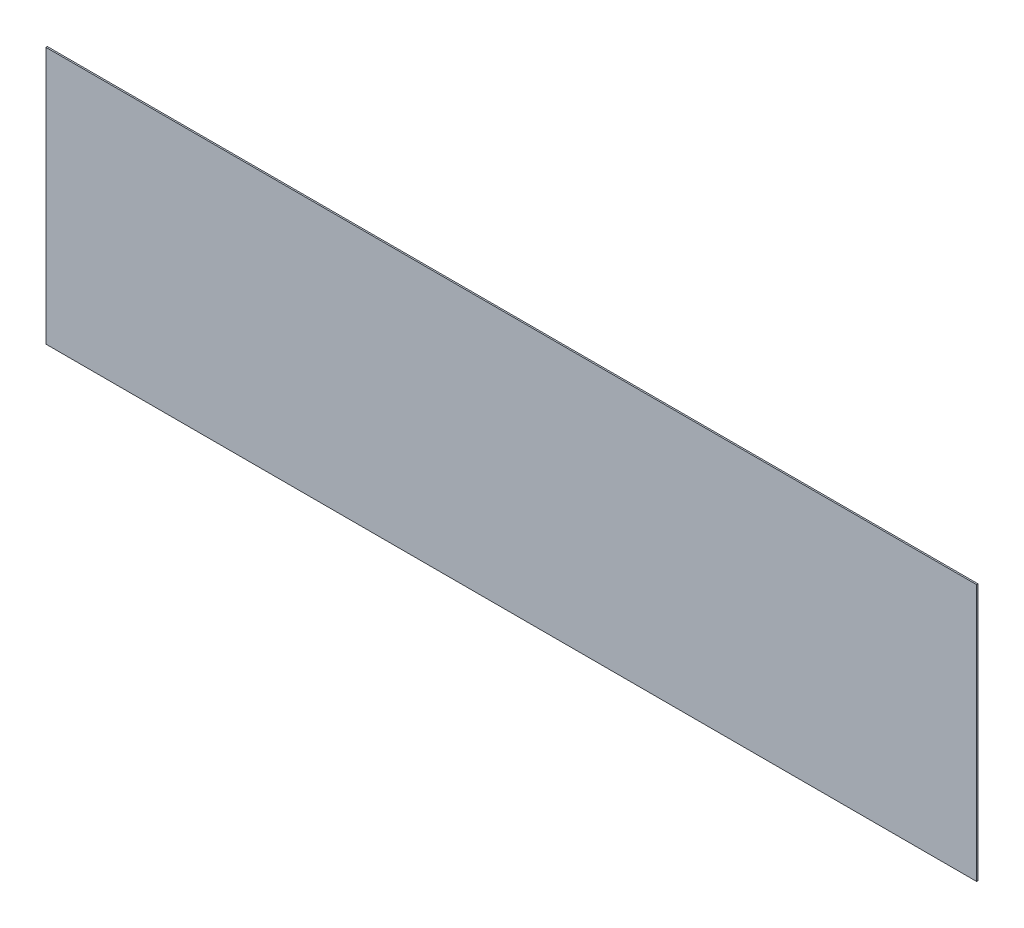
SolidWorks part; units mm, degrees
ref_plane "Front Plane" through (0, 0, 0) normal (0, 0, 1) x (1, 0, 0)
ref_plane "Top Plane" through (0, 0, 0) normal (0, 1, 0) x (1, 0, 0)
ref_plane "Right Plane" through (0, 0, 0) normal (1, 0, 0) x (0, 0, -1)
other "Configuration Table"
sketch "Sketch1" plane through (0, 0, 0) normal (0, 0, 1) x (1, 0, 0)
  line L1 (702, 1469) -> (1350, 1469)
  line L2 (702, 1469) -> (702, 1648)
  line L3 (702, 1648) -> (1350, 1648)
  line L4 (1350, 1469) -> (1350, 1648)
extrude "DET2_arka_ic_sac_1" add sketch "Sketch1" against normal blind 1 from offset 757.5 separate body
